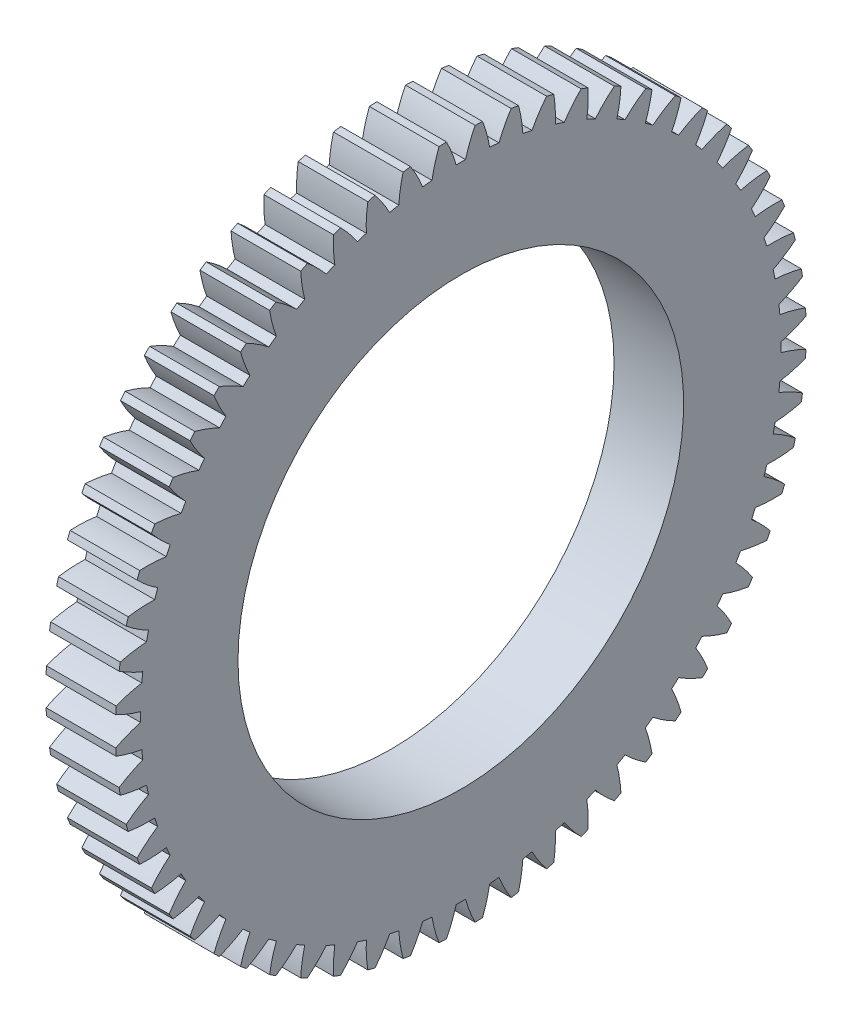
SolidWorks part; units mm, degrees
ref_plane "Plane1" through (0, 0, 0) normal (0, 0, 1) x (1, 0, 0)
ref_plane "Plane2" through (0, 0, 0) normal (0, 1, 0) x (1, 0, 0)
ref_plane "Plane3" through (0, 0, 0) normal (1, 0, 0) x (0, 0, -1)
sketch "HoldingSke" plane through (0, 0, 0) normal (0, 1, 0) x (1, 0, 0)
  line L0 (0, 0) -> (0.125, -0.2165)
  line L1 (-15, 0) -> (100, 0) construction
  line L2 (0, 0) -> (-2.1039, 2.3779)
  line L3 (0, 0) -> (-11.863, 4.5341)
  line L4 (0, 0) -> (4.318, 7.479)
  line L5 (0, 0) -> (-46.8476, -17.4728)
  line L6 (0, 0) -> (-20.7241, -13.9826)
  line L7 (-2.1039, 2.3779) -> (8.6586, 51.2059)
  line L8 (-76.2, 54.61) -> (-66.8, 54.61)
  line L9 (-71.009, 38.7566) -> (-53.1078, 45.2721)
  line L10 (-76.2, 71.12) -> (104.1128, 71.12)
  line L11 (0, 0) -> (-25, 0)
  line L12 (-76.2, 101.6) -> (-76.073, 101.6)
  line L13 (24.9733, 27.94) -> (52.9518, 28.4284)
  line L14 (24.9733, 27.94) -> (24.9743, 27.94)
  line L15 (24.9733, 27.94) -> (100.4006, 29.5858)
  line L16 (-63.627, -4) -> (-12.827, -4)
  circle A0 centre (0, 0) radius 80
  circle A1 centre (0, 0) radius 37.5
  circle A2 centre (0, 0) radius 37.5
  circle A3 centre (0, 0) radius 80
  dimension "MHD" = 75
  dimension "Hub_dia" = 75
  dimension "Bore" = 160
  dimension "MBD" = 160
  dimension "Pitch" = 0.25
  dimension "Overall_len" = 50
  dimension "Thickness" = 25
  dimension "OAL" = 50.0001
  dimension "Ap" = 20
  dimension "H" = 19.05
  dimension "Pitch_radius" = 180.3128
  dimension "Width" = 25
  dimension "Backlash" = 0.127
  dimension "Addendum_fac" = 1
  dimension "Dedendum_fac" = 1.25
  dimension "Clearance_fac" = 0.25
  dimension "Dedendum_add" = 0.001
  dimension "Module" = 4
sketch "BasProSke" plane through (0, 0, 0) normal (0, 1, 0) x (1, 0, 0)
  line L0 (-10, 0) -> (60, 0) construction
  line L1 (0, 0) -> (0, 124)
  line L2 (0, 0) -> (25, 0)
  line L3 (25, 0) -> (25, 124)
  line L4 (25, 124) -> (0, 124)
  dimension "Thickness" = 25
revolve "Base-Revolve" add sketch "BasProSke" angle 360 about L0
sketch "TooCutSke" plane through (0, 0, 0) normal (1, 0, 0) x (0, 0, -1)
  line L1 (0, 0) -> (0, 107) construction
  line L2 (0, 0) -> (-3.3635, 119.9529) construction
  line L3 (0, 0) -> (-12.5569, 239.6002) construction
  line L4 (-3.3635, 119.9529) -> (-6.2785, 119.8001) construction
  arc A0 (1.6795, 114.9867) -> (-1.6795, 114.9867) centre (0, 0) ccw
  arc A1 (5.1673, 123.9177) -> (-5.1673, 123.9177) centre (0, 0) ccw
  circle A2 centre (0, 0) radius 120 construction
  circle A3 centre (0, 0) radius 112.7631 construction
  arc A4 (-1.6795, 114.9867) -> (-5.1673, 123.9177) centre (-47.9113, 102.0785) ccw
  arc A5 (5.1673, 123.9177) -> (1.6795, 114.9867) centre (47.9113, 102.0785) ccw
  dimension "Half_CT" = 2.919
extrude "ToothCut" cut sketch "TooCutSke" along normal through all
fillet "Breaks" [suppressed] radius 0.08
fillet "RootFillets" [suppressed] radius 1.001
pattern_circular "TeethCuts" count 60 every 6 about axis through (-10, 0, 0) along (1, 0, 0) of "ToothCut", "RootFillets", "Breaks"
sketch "HubNeaOneSke" plane through (0, 0, 0) normal (-1, 0, 0) x (0, 0, 1)
  circle A0 centre (0, 0) radius 37.5
  dimension "Diameter" = 75
extrude "HubNearOne" [suppressed] add sketch "HubNeaOneSke" along normal blind 25.0001
sketch "HubNeaBotSke" plane through (0, 0, 0) normal (-1, 0, 0) x (0, 0, 1)
  circle A0 centre (0, 0) radius 37.5
  dimension "Diameter" = 75
extrude "HubNearBoth" [suppressed] add sketch "HubNeaBotSke" along normal blind 12.5
ref_plane "FarPln" through (25, 0, 0) normal (1, 0, 0) x (0, 0, -1)
sketch "HubFarSke" plane through (25, 0, 0) normal (1, 0, 0) x (0, 0, -1)
  circle A0 centre (0, 0) radius 37.5
  dimension "Diameter" = 75
extrude "HubFar" [suppressed] add sketch "HubFarSke" along normal blind 12.5
sketch "BorSke" plane through (0, 0, 0) normal (1, 0, 0) x (0, 0, -1)
  circle A0 centre (0, 0) radius 80
  dimension "Diameter" = 160
extrude "Bore" cut sketch "BorSke" along normal mid plane 100.0001
sketch "KeySke" plane through (0, 0, 0) normal (1, 0, 0) x (0, 0, -1)
  line L0 (-20, 0) -> (-20, 89.4)
  line L1 (-20, 89.4) -> (20, 89.4)
  line L2 (20, 89.4) -> (20, 0)
  line L3 (0, 0) -> (0, 34) construction
  line L4 (-20, 0) -> (20, 0)
extrude "Keyway" [suppressed] cut sketch "KeySke" along normal mid plane 100.0001
pattern_circular "Keyway2" [suppressed] count 2 every 90 about axis through (-10, 0, 0) along (1, 0, 0)
equation "' \"Module@HoldingSke\" = 6.35"
equation "' \"Num_teeth@HoldingSke\" = 12"
equation "' \"Ap@HoldingSke\" =  20"
equation "' \"Ap@HoldingSke\" = 20"
equation "' \"Width@HoldingSke\" = 0.5 * 25.4"
equation "' \"Hub_dia@HoldingSke\"= 1 * 25.4"
equation "' \"Hub_dia@HoldingSke\" = 1 * 25.4"
equation "' \"Overall_len@HoldingSke\" = 1.0 * 25.4"
equation "' \"Bore@HoldingSke\" = 0.75 * 25.4"
equation "' \"T_dim@HoldingSke\" = 0.1 * 25.4"
equation "' \"Width@KeySke\" = 0.25 * 25.4"
equation "' \"Show_teeth@HoldingSke\" = 13"
equation "' \"Backlash@HoldingSke\" = 0.009 * 25.4"
equation "' \"Addendum_fac@HoldingSke\" = 1.0"
equation "' \"Dedendum_fac@HoldingSke\" = 1.25"
equation "' \"Dedendum_add@HoldingSke\" = 0.00005 * 25.4"
equation "' \"Clearance_fac@HoldingSke\" = 0.25"
equation "\"Pitch@HoldingSke\" = 1 / \"Module@HoldingSke\""
equation "\"Overcut_dia@TooCutSke\" = (\"Num_teeth@HoldingSke\" + 2 * \"Addendum_fac@HoldingSke\") / \"Pitch@HoldingSke\" + 0.002 * 25.4"
equation "\"Pitch_dia@TooCutSke\" = \"Num_teeth@HoldingSke\" / \"Pitch@HoldingSke\""
equation "\"Base_dia@TooCutSke\" = \"Num_teeth@HoldingSke\" / \"Pitch@HoldingSke\" * cos((\"Ap@HoldingSke\"  * 3.14159265 / 180))"
equation "\"Root_dia@TooCutSke\" = (\"Num_teeth@HoldingSke\" + 2) / \"Pitch@HoldingSke\" - 2 * (\"Addendum_fac@HoldingSke\" + \"Dedendum_fac@HoldingSke\") / \"Pitch@HoldingSke\" - \"Dedendum_add@HoldingSke\" * 2"
equation "\"Half_ang@TooCutSke\" = 180 / \"Num_teeth@HoldingSke\""
equation "\"Half_CT@TooCutSke\" = \"Num_teeth@HoldingSke\" / \"Pitch@HoldingSke\" * sin((3.14159265 / 2 / \"Num_teeth@HoldingSke\")) / 2 - 7 * \"Backlash@HoldingSke\" / 4"
equation "\"Flank_rad@TooCutSke\" = \"Num_teeth@HoldingSke\" / \"Pitch@HoldingSke\" / 5"
equation "\"Radius@RootFillets\" = \"Clearance_fac@HoldingSke\" / \"Pitch@HoldingSke\" + \"Dedendum_add@HoldingSke\""
equation "\"Break_rad@Breaks\" = 0.02 / \"Pitch@HoldingSke\""
equation "\"Thickness@HoldingSke\" = \"Width@HoldingSke\""
equation "\"OAL@HoldingSke\" = \"Thickness@HoldingSke\""
equation "\"MHD@HoldingSke\" = (\"Num_teeth@HoldingSke\" + 2) / \"Pitch@HoldingSke\" - 2 * (\"Addendum_fac@HoldingSke\" + \"Dedendum_fac@HoldingSke\")  / \"Pitch@HoldingSke\" - \"Dedendum_add@HoldingSke\" * 2"
equation "\"MBD@HoldingSke\" = (\"Num_teeth@HoldingSke\" + 2) / \"Pitch@HoldingSke\" - 2 * (\"Addendum_fac@HoldingSke\" + \"Dedendum_fac@HoldingSke\")  / \"Pitch@HoldingSke\" - \"Dedendum_add@HoldingSke\" * 2 - 0.002 * 25.4"
equation "\"MHD@HoldingSke\" = ((sgn( \"MHD@HoldingSke\" - \"Hub_dia@HoldingSke\" )-1)*( \"MHD@HoldingSke\" - \"Hub_dia@HoldingSke\" ))/-2+ \"Hub_dia@HoldingSke\""
equation "\"MBD@HoldingSke\" = ((sgn( \"MBD@HoldingSke\" - \"Bore@HoldingSke\" )-1)*( \"MBD@HoldingSke\" - \"Bore@HoldingSke\" ))/-2+ \"Bore@HoldingSke\""
equation "\"OAL@HoldingSke\" = ((sgn( \"OAL@HoldingSke\" - \"Overall_len@HoldingSke\" )+1)*( \"OAL@HoldingSke\" - \"Overall_len@HoldingSke\" ))/2 + \"Overall_len@HoldingSke\" + 0.000002 * 25.4"
equation "\"Num_teeth@TeethCuts\" = int( \"Show_teeth@HoldingSke\" ) + 1"
equation "\"Num_teeth@TeethCuts\" = ((sgn( \"Num_teeth@TeethCuts\" - \"Num_teeth@HoldingSke\" )-1)*( \"Num_teeth@TeethCuts\" - \"Num_teeth@HoldingSke\" ))/-2+ \"Num_teeth@HoldingSke\""
equation "\"Num_teeth@TeethCuts\" = ((sgn( \"Num_teeth@TeethCuts\" - 2.0)+1)*( \"Num_teeth@TeethCuts\" - 2.0))/2 +2.0"
equation "\"Angle@TeethCuts\" = 360.0 / \"Num_teeth@HoldingSke\""
equation "\"Diameter@BasProSke\" = (\"Num_teeth@HoldingSke\" + 2 * \"Addendum_fac@HoldingSke\") / \"Pitch@HoldingSke\""
equation "\"Thickness@BasProSke\"  = \"Thickness@HoldingSke\""
equation "' \"Fillet_rad@BasProSke\" =  \"Thickness@HoldingSke\" * 0.05"
equation "' \"Fillet_rad@BasProSke\" = \"Thickness@HoldingSke\" * 0.05"
equation "\"MHD@HoldingSke\" = ((sgn( \"MHD@HoldingSke\" - \"Root_dia@TooCutSke\" )-1)*( \"MHD@HoldingSke\" - \"Root_dia@TooCutSke\" ))/-2+ \"Root_dia@TooCutSke\""
equation "\"Diameter@HubNeaOneSke\" = \"MHD@HoldingSke\""
equation "\"Length@HubNearOne\" = \"OAL@HoldingSke\" - \"Thickness@BasProSke\""
equation "\"Diameter@HubNeaBotSke\" = \"MHD@HoldingSke\""
equation "\"Length@HubNearBoth\" = ( \"OAL@HoldingSke\" - \"Thickness@BasProSke\" ) / 2.0"
equation "\"Thickness@FarPln\" = \"Thickness@BasProSke\""
equation "\"Diameter@HubFarSke\" = \"MHD@HoldingSke\""
equation "\"Length@HubFar\" = ( \"OAL@HoldingSke\" - \"Thickness@BasProSke\" ) / 2.0"
equation "\"Diameter@BorSke\" = \"MBD@HoldingSke\""
equation "\"D1@Bore\" = \"OAL@HoldingSke\" * 2.0"
equation "\"D1@Keyway\" = \"OAL@HoldingSke\" * 2.0"
equation "\"Offset@KeySke\" = \"T_dim@HoldingSke\" + \"MBD@HoldingSke\" / 2.0"
